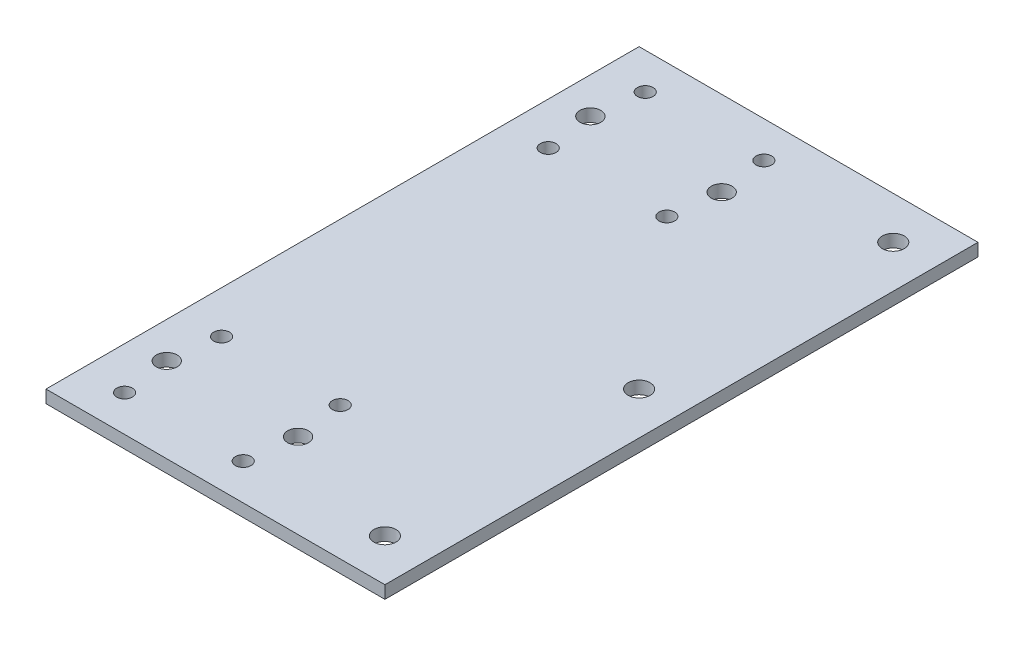
SolidWorks part; units mm, degrees
ref_plane "前视基准面" through (0, 0, 0) normal (0, 0, 1) x (1, 0, 0)
ref_plane "上视基准面" through (0, 0, 0) normal (0, 1, 0) x (1, 0, 0)
ref_plane "右视基准面" through (0, 0, 0) normal (1, 0, 0) x (0, 0, -1)
other "Configuration Table"
sketch "草图1" plane through (0, 0, 0) normal (0, 1, 0) x (1, 0, 0)
  line L0 (-40, 0) -> (49960, 0) construction
  line L1 (-40, -70) -> (40, -70)
  line L2 (-40, -70) -> (-40, 70)
  line L3 (-40, 70) -> (40, 70)
  line L4 (40, -70) -> (40, 70)
  line L5 (-40, -70) -> (40, 70) construction
  line L6 (-40, 70) -> (40, -70) construction
  line L7 (-40, 70) -> (8, 70)
  line L8 (-40, 70) -> (-40, 30)
  line L9 (-40, 30) -> (8, 30)
  line L10 (8, 70) -> (8, 30)
  line L11 (-40, -70) -> (8, -70)
  line L12 (-40, -70) -> (-40, -30)
  line L13 (-40, -30) -> (8, -30)
  line L14 (8, -70) -> (8, -30)
  line L15 (-40, 70) -> (-30, 70)
  line L16 (-40, 70) -> (-40, 61.45)
  line L17 (-40, 61.45) -> (-30, 61.45)
  line L18 (-30, 70) -> (-30, 61.45)
  line L19 (-16, 30) -> (-16, 50030) construction
  line L20 (8, 50) -> (-0.5, 50) construction
  line L22 (40, 70) -> (30, 70)
  line L23 (40, 70) -> (40, 60)
  line L24 (40, 60) -> (30, 60)
  line L25 (30, 70) -> (30, 60)
  circle A0 centre (-30, 61.45) radius 1.85
  circle A1 centre (-2, 61.45) radius 1.85
  circle A2 centre (-2, 38.55) radius 1.85
  circle A3 centre (-30, 38.55) radius 1.85
  circle A4 centre (-0.5, 50) radius 2.45
  circle A5 centre (-31.5, 50) radius 2.45
  circle A6 centre (-2, -38.55) radius 1.85
  circle A7 centre (-0.5, -50) radius 2.45
  circle A8 centre (-2, -61.45) radius 1.85
  circle A9 centre (-30, -38.55) radius 1.85
  circle A10 centre (-31.5, -50) radius 2.45
  circle A11 centre (-30, -61.45) radius 1.85
  circle A12 centre (30, 60) radius 2.5
  circle A13 centre (30, 0) radius 2.5
  circle A14 centre (30, -60) radius 2.5
  point P0 (0, 0)
  point P21 (-16, 30)
  point P33 (-40, 0)
  dimension "D9" = 3.7
  dimension "D11" = 4.9
  dimension "D14" = 5
  dimension "D1" = 80
  dimension "D2" = 140
  dimension "D3" = 40
  dimension "D4" = 48
  dimension "D5" = 48
  dimension "D6" = 40
  dimension "D7" = 10
  dimension "D8" = 8.55
  dimension "D10" = 8.5
  dimension "D12" = 10
  dimension "D13" = 10
  dimension "D15" = 3
extrude "凸台-拉伸1" add sketch "草图1" along normal blind 3 contours A12 L25 L3 L10 L9 L2 L13 L14 L1 L4 L24 A14 A13 | A12 L24 L4 L3 L25 | A0 L17 L2 L9 L10 L7 L18 A3 A2 A1 A4 A5 | A0 L18 L3 L8 L17 | L1 L14 L13 L2 A7 A6 A8 A9 A10 A11
sketch "草图2" plane through (0, 3, 0) normal (0, 1, 0) x (1, 0, 0)
  circle A0 centre (30, 60) radius 2.6
  circle A1 centre (30, 0) radius 2.6
  circle A2 centre (30, -60) radius 2.6
  dimension "D1" = 5.2
  dimension "D2" = 3
extrude "切除-拉伸1" cut sketch "草图2" against normal blind 10
